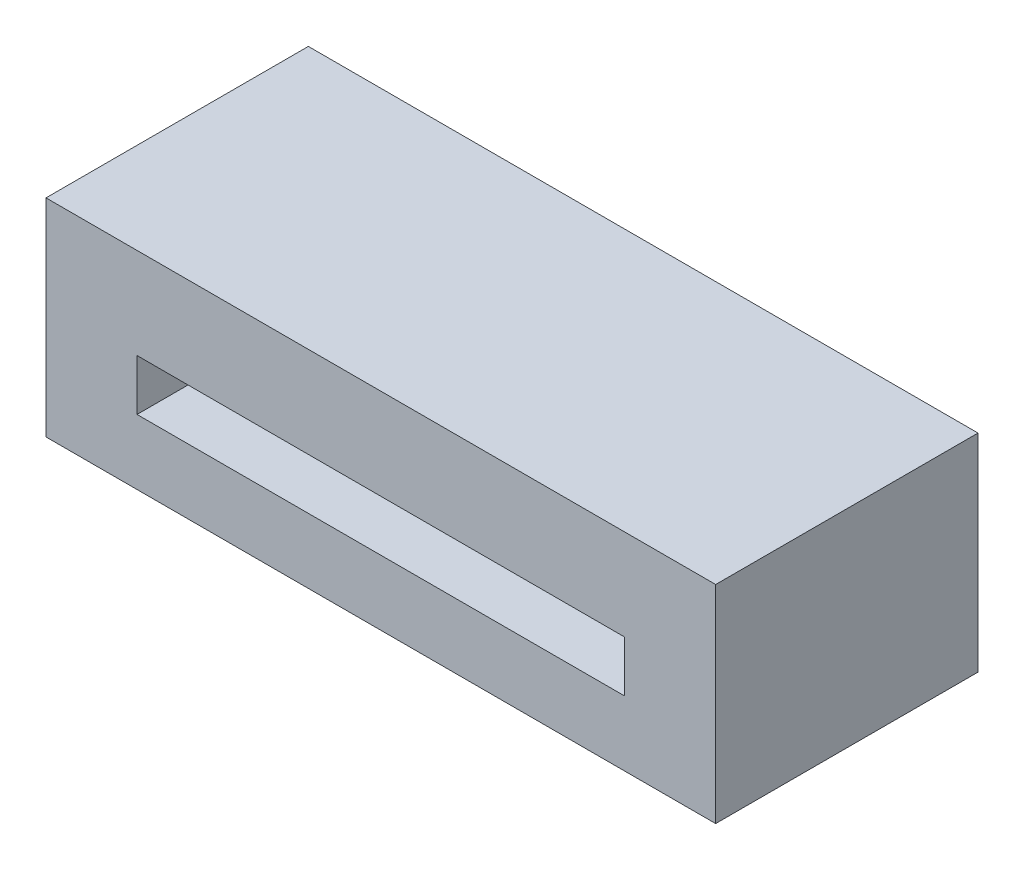
SolidWorks part; units mm, degrees
ref_plane "Plan de face" through (0, 0, 0) normal (0, 0, 1) x (1, 0, 0)
ref_plane "Plan de dessus" through (0, 0, 0) normal (0, 1, 0) x (1, 0, 0)
ref_plane "Plan de droite" through (0, 0, 0) normal (1, 0, 0) x (0, 0, -1)
sketch "Esquisse1" plane through (0, 0, 0) normal (0, 1, 0) x (1, 0, 0)
  line L1 (0, 0) -> (15, 0)
  line L2 (0, 0) -> (0, 8.07)
  line L3 (0, 8.07) -> (15, 8.07)
  line L4 (15, 0) -> (15, 8.07)
extrude "Boss.-Extru.1" add sketch "Esquisse1" along normal blind 2.8
sketch "Esquisse4" plane through (0, 2.8, 0) normal (0, 1, 0) x (1, 0, 0)
  line L0 (0, 4.445) -> (0, 0) construction
  line L1 (0, 0) -> (17.8, 0) construction
  line L2 (17.8, 0) -> (17.8, 4.445) construction
  line L3 (17.8, 4.445) -> (8.905, 4.445) construction
  line L4 (8.905, 4.445) -> (8.905, 0.5) construction
  line L5 (8.905, 0.5) -> (6.405, 0.5) construction
  line L6 (6.405, 0.5) -> (6.405, 4.445) construction
  line L7 (6.405, 4.445) -> (0, 4.445) construction
  line L9 (15, 8.07) -> (17.8, 8.07)
  line L10 (17.8, 8.07) -> (17.8, 0)
  line L11 (17.8, 0) -> (15, 0)
  line L12 (15, 0) -> (15, 8.07)
  line L13 (7.5, 8.07) -> (7.5, 0) construction
  line L14 (-2.8, 0) -> (0, 0)
  line L15 (-2.8, 8.07) -> (-2.8, 0)
  line L16 (0, 8.07) -> (-2.8, 8.07)
  line L17 (0, 0) -> (0, 8.07)
extrude "Boss.-Extru.3" add sketch "Esquisse4" against normal blind 6.37
sketch "Esquisse5" plane through (0, 0, 0) normal (1, 0, 0) x (0, 0, -1)
  line L0 (8.07, -0.2104) -> (8.07, -1.57)
  line L1 (8.07, -1.57) -> (5.5224, -1.57)
  line L2 (8.07, 0) -> (0, 0) construction
  line L3 (5.5224, -1.57) -> (0, -1.57)
  line L4 (0, -1.57) -> (0, 0)
  line L5 (0, 0) -> (8.07, 0)
  line L6 (8.07, 0) -> (8.07, -0.2104)
  line L7 (0, -3.57) -> (0, -1.57)
  line L8 (8.07, -1.57) -> (8.07, -3.57)
  line L9 (8.07, -3.57) -> (0, -3.57)
  line M2 (8.07, -3.57) -> (8.07, 0)
  line M4 (0, 0) -> (0, -3.57)
  line M5 (0, -3.57) -> (8.07, -3.57)
  dimension "D1" = 1.57
extrude "Boss.-Extru.4" add sketch "Esquisse5" along normal blind 15 contours L1 L3 M4 M5 M2
sketch "Esquisse6" plane through (0, -3.57, 0) normal (0, -1, 0) x (1, 0, 0)
  line L0 (6.405, -3.6089) -> (0, -3.6089) construction
  line L1 (0, -3.6089) -> (15, -3.6089) construction
  line L2 (8.905, -3.6089) -> (8.905, -7.5539)
  line L3 (8.905, -7.5539) -> (6.405, -7.5539)
  line L4 (6.405, -7.5539) -> (6.405, -3.6089)
  line L5 (15, -3.6089) -> (15, -8.0539)
  line L6 (15, -8.0539) -> (0, -8.0539)
  line L7 (0, -8.0539) -> (0, -3.6089)
  line L8 (0, -3.6089) -> (6.405, -3.6089)
  line L9 (6.405, -7.5539) -> (8.905, -7.5539)
  line L10 (8.905, -3.6089) -> (15, -3.6089)
  line L12 (6.405, -3.6089) -> (8.905, -3.6089)
extrude "Enlèv. mat.-Extru.1" cut sketch "Esquisse6" against normal blind 3 contours L12 L4 L3 L2
sketch "Esquisse7" plane through (0, -3.57, 0) normal (0, -1, 0) x (1, 0, 0)
  line L0 (8.905, -7.5539) -> (14.9726, -7.5539)
  line L1 (14.9726, -7.5539) -> (14.9726, -2.5403)
  line L2 (8.905, -3.6089) -> (14.9726, -3.6089)
  line L3 (7.6415, -7.3604) -> (7.655, -3.6089) construction
  line L4 (6.405, -3.5999) -> (0.3376, -3.5562)
  line L5 (0.3092, -7.5011) -> (0.3453, -2.4877)
  line L6 (6.3766, -7.5448) -> (0.3092, -7.5011)
  line L7 (14.9726, -2.5403) -> (14.9726, 0)
  line L8 (14.9726, 0) -> (0, 0)
  line L9 (0, 0) -> (0, -7.5011)
  line L10 (0, -7.5011) -> (0.3092, -7.5011)
  line L11 (0.3376, -3.5562) -> (0, -3.5562)
  line L12 (0, -7.5011) -> (0.3092, -7.5011)
  line L13 (0.3376, -3.5562) -> (0, -3.5562)
  line L14 (0, -3.5562) -> (6.405, -3.5999)
  line L15 (8.905, -3.6089) -> (8.905, -7.5539)
  line L16 (6.405, -3.5999) -> (8.905, -3.6089)
